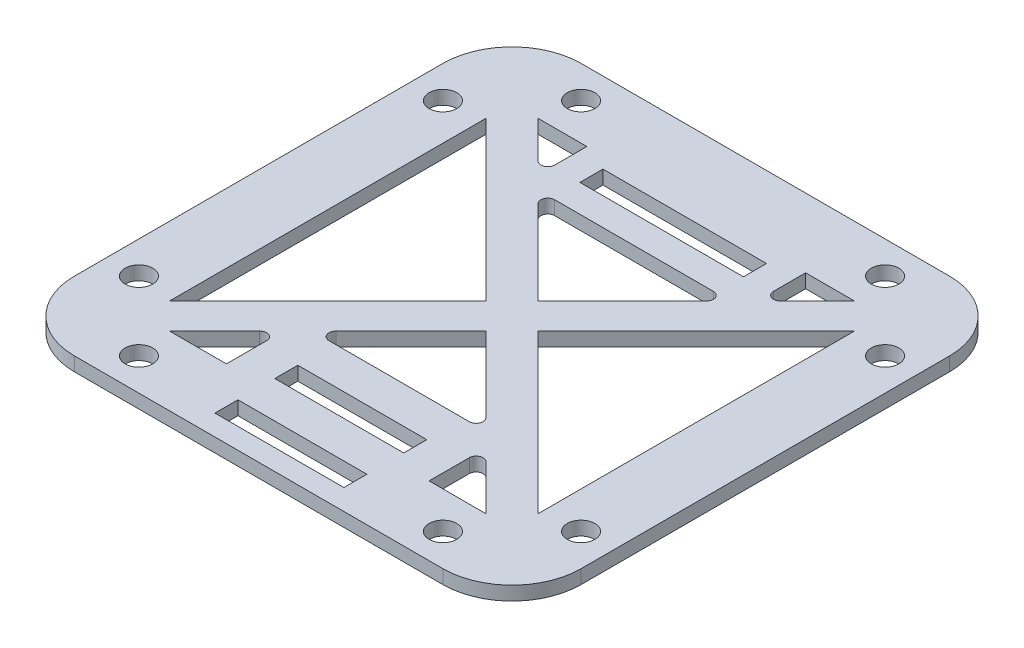
SolidWorks part; units mm, degrees
material "MDF"
ref_plane "Front Plane" through (0, 0, 0) normal (0, 0, 1) x (1, 0, 0)
ref_plane "Top Plane" through (0, 0, 0) normal (0, 1, 0) x (1, 0, 0)
ref_plane "Right Plane" through (0, 0, 0) normal (1, 0, 0) x (0, 0, -1)
sketch "Sketch1" plane through (0, 0, 0) normal (0, 1, 0) x (1, 0, 0)
  line L0 (55.8725, -40.1246) -> (55.8725, 39.8754)
  line L1 (40.8725, 54.8754) -> (-39.1275, 54.8754)
  line L2 (-54.1275, 39.8754) -> (-54.1275, -40.1246)
  line L3 (-39.1275, -55.1246) -> (40.8725, -55.1246)
  circle A0 centre (48.8725, 32.8754) radius 3
  circle A1 centre (-47.1275, -33.1246) radius 3
  circle A2 centre (-32.1275, -48.1246) radius 3
  circle A3 centre (33.8725, -48.1246) radius 3
  circle A4 centre (48.8725, -33.1246) radius 3
  circle A5 centre (33.8725, 47.8754) radius 3
  circle A6 centre (-32.1275, 47.8754) radius 3
  circle A7 centre (-47.1275, 32.8754) radius 3
  arc A8 (55.8725, 39.8754) -> (40.8725, 54.8754) centre (40.8725, 39.8754) ccw
  arc A9 (-39.1275, 54.8754) -> (-54.1275, 39.8754) centre (-39.1275, 39.8754) ccw
  arc A10 (-54.1275, -40.1246) -> (-39.1275, -55.1246) centre (-39.1275, -40.1246) ccw
  arc A11 (40.8725, -55.1246) -> (55.8725, -40.1246) centre (40.8725, -40.1246) ccw
extrude "Boss-Extrude1" add sketch "Sketch1" along normal blind 3
sketch "Sketch2" plane through (0, 3, 0) normal (0, 1, 0) x (1, 0, 0)
  line L0 (0.8725, 54.8754) -> (0.8725, 34.8754) construction
  line L1 (40.8725, 54.8754) -> (-39.1275, 54.8754) construction
  line L2 (0.8725, -55.1246) -> (0.8725, -35.1246) construction
  line L3 (-39.1275, -55.1246) -> (40.8725, -55.1246) construction
  line L5 (-13.1275, -37.6246) -> (14.8725, -37.6246)
  line L6 (-13.1275, -37.6246) -> (-13.1275, -32.6246)
  line L7 (-13.1275, -32.6246) -> (14.8725, -32.6246)
  line L8 (14.8725, -37.6246) -> (14.8725, -32.6246)
  line L9 (-13.1275, -37.6246) -> (14.8725, -32.6246) construction
  line L10 (-13.1275, -32.6246) -> (14.8725, -37.6246) construction
  line L11 (-16.8775, 32.3754) -> (18.6225, 32.3754)
  line L12 (-16.8775, 32.3754) -> (-16.8775, 37.3754)
  line L13 (-16.8775, 37.3754) -> (18.6225, 37.3754)
  line L14 (18.6225, 32.3754) -> (18.6225, 37.3754)
  line L15 (-16.8775, 32.3754) -> (18.6225, 37.3754) construction
  line L16 (-16.8775, 37.3754) -> (18.6225, 32.3754) construction
  dimension "D1" = 20
  dimension "D2" = 20
  dimension "D3" = 35.5
  dimension "D4" = 5
  dimension "D5" = 28
  dimension "D6" = 5
extrude "Cut-Extrude1" cut sketch "Sketch2" against normal through all
sketch "Sketch3" plane through (0, 3, 0) normal (0, 1, 0) x (1, 0, 0)
  line L0 (-39.1275, 34.2185) -> (-4.7844, -0.1246)
  line L1 (-33.4707, -40.1246) -> (-21.1275, -40.1246)
  line L2 (-39.1275, -34.4678) -> (-39.1275, 34.2185)
  line L3 (-33.4707, 39.8754) -> (-22.8775, 39.8754)
  line L4 (40.8725, -34.4678) -> (40.8725, 34.2185)
  line L5 (-39.1275, -40.1246) -> (40.8725, 39.8754) construction
  line L6 (-39.1275, 39.8754) -> (40.8725, -40.1246) construction
  line L7 (-33.4707, -40.1246) -> (-21.1275, -27.7815)
  line L8 (-33.4707, 39.8754) -> (-22.8775, 29.2822)
  line L9 (-39.1275, -34.4678) -> (-4.7844, -0.1246)
  line L16 (40.8725, 54.8754) -> (-39.1275, 54.8754) construction
  line L18 (55.8725, -40.1246) -> (55.8725, 39.8754) construction
  line L44 (24.6225, 26.3754) -> (24.6225, 37.3754)
  line L45 (-22.8775, 26.3754) -> (24.6225, 26.3754)
  line L46 (-22.8775, 37.3754) -> (-22.8775, 26.3754)
  line L47 (24.6225, 29.2822) -> (24.6225, 39.8754)
  line L48 (-19.9707, 26.3754) -> (21.7156, 26.3754)
  line L49 (-22.8775, 39.8754) -> (-22.8775, 29.2822)
  line L53 (22.8725, -40.1246) -> (35.2156, -40.1246)
  line L54 (-41.956, 37.0469) -> (38.044, -42.9531) construction
  line L55 (-36.2991, 42.7038) -> (43.7009, -37.2962) construction
  line L56 (22.8725, -37.6246) -> (22.8725, -24.6246)
  line L57 (22.8725, -24.6246) -> (-21.1275, -24.6246)
  line L58 (-21.1275, -24.6246) -> (-21.1275, -37.6246)
  line L59 (22.8725, -40.1246) -> (22.8725, -27.7815)
  line L60 (19.7156, -24.6246) -> (-17.9707, -24.6246)
  line L61 (-21.1275, -27.7815) -> (-21.1275, -40.1246)
  line L62 (22.8725, -27.7815) -> (35.2156, -40.1246)
  line L63 (6.5293, -0.1246) -> (40.8725, 34.2185)
  line L64 (-36.2991, -42.9531) -> (43.7009, 37.0469) construction
  line L65 (6.5293, -0.1246) -> (40.8725, -34.4678)
  line L66 (0.8725, 5.5322) -> (21.7156, 26.3754)
  line L67 (-41.956, -37.2962) -> (38.044, 42.7038) construction
  line L68 (0.8725, -5.7815) -> (19.7156, -24.6246)
  line L69 (-17.9707, -24.6246) -> (0.8725, -5.7815)
  line L70 (-19.9707, 26.3754) -> (0.8725, 5.5322)
  line L71 (24.6225, 39.8754) -> (35.2156, 39.8754)
  line L72 (24.6225, 29.2822) -> (35.2156, 39.8754)
  point P0 (0.8725, -0.1246)
  point P14 (-0.8258, 0)
  point P22 (0, 0)
  dimension "D1" = 80
  dimension "D2" = 80
  dimension "D5" = 15
  dimension "D6" = 15
  dimension "D3" = 4
  dimension "D4" = 4
  dimension "D7" = 6
  dimension "D8" = 8
extrude "Cut-Extrude2" cut sketch "Sketch3" against normal through all
fillet "Fillet1" radius 1.5 8 edges at (-17.9707, 1.5, 24.6246) (-21.1275, 1.5, 27.7815) (22.8725, 1.5, 27.7815) (19.7156, 1.5, 24.6246) (24.6225, 1.5, -29.2822) (-22.8775, 1.5, -29.2822) (21.7156, 1.5, -26.3754) (-19.9707, 1.5, -26.3754)
sketch "Sketch4" plane through (0, 3, 0) normal (0, 1, 0) x (1, 0, 0)
  line L0 (-20.6963, -41.6246) -> (19.6346, -41.6246) construction
  line L1 (-13.1275, -37.6246) -> (14.8725, -37.6246) construction
  line L2 (14.8725, -37.6246) -> (14.8725, -32.6246) construction
  line L3 (-13.1275, -32.6246) -> (-13.1275, -37.6246) construction
  line L4 (14.8725, -32.6246) -> (-13.1275, -32.6246) construction
  line L5 (14.8725, -37.6246) -> (14.8725, -32.6246) construction
  line L6 (-13.1275, -37.6246) -> (14.8725, -37.6246) construction
  line L7 (-13.1275, -32.6246) -> (-13.1275, -37.6246) construction
  line L8 (14.8725, -32.6246) -> (-13.1275, -32.6246) construction
  line L9 (14.8725, -50.6246) -> (-13.1275, -50.6246)
  line L10 (-13.1275, -50.6246) -> (-13.1275, -45.6246)
  line L11 (-13.1275, -45.6246) -> (14.8725, -45.6246)
  line L12 (14.8725, -45.6246) -> (14.8725, -50.6246)
  dimension "D1" = 4
extrude "Cut-Extrude3" cut sketch "Sketch4" against normal through all
